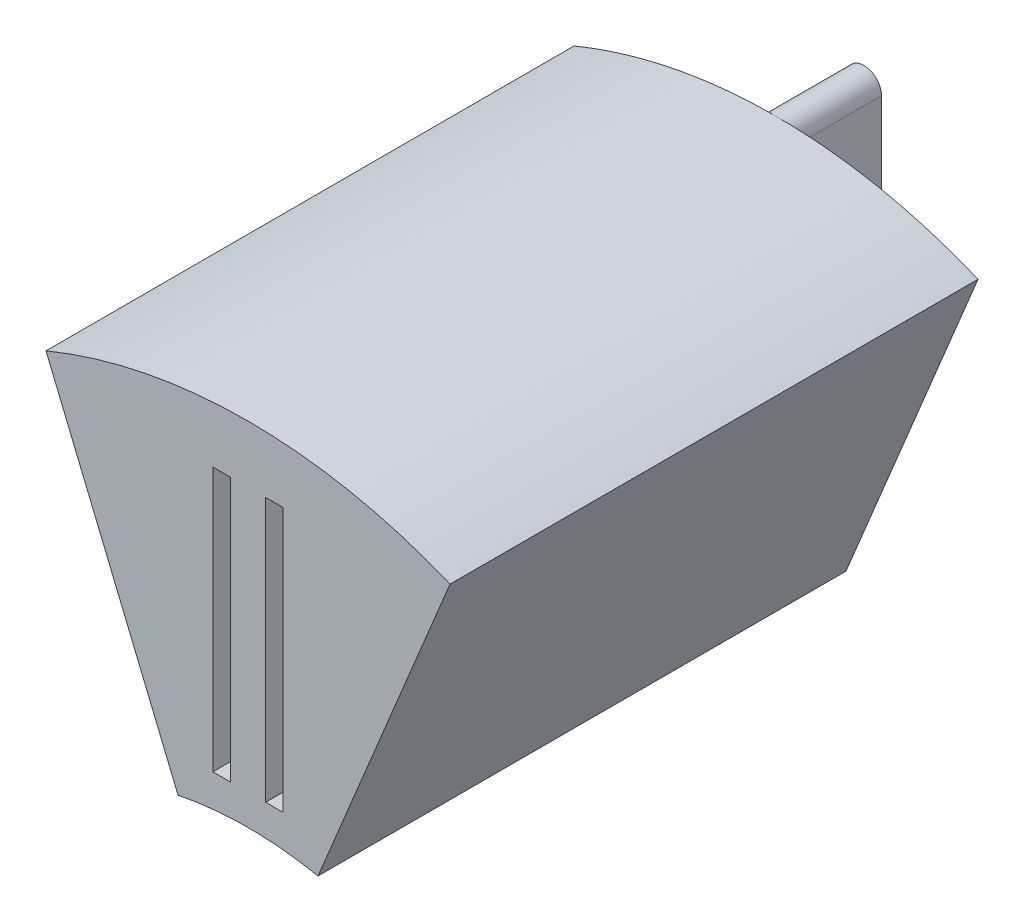
SolidWorks part; units mm, degrees
ref_plane "Ön Düzlem" through (0, 0, 0) normal (0, 0, 1) x (1, 0, 0)
ref_plane "Üst Düzlem" through (0, 0, 0) normal (0, 1, 0) x (1, 0, 0)
ref_plane "Sağ Düzlem" through (0, 0, 0) normal (1, 0, 0) x (0, 0, -1)
sketch "Sketch1" plane through (0, 0, 0) normal (0, 0, 1) x (1, 0, 0)
  line L0 (1.1481, 2.7716) -> (0.3827, 0.9239)
  line L6 (-1.1481, 2.7716) -> (-0.3827, 0.9239)
  line L7 (-1.1481, 2.7716) -> (0, 0) construction
  line L8 (0, 0) -> (1.1481, 2.7716) construction
  line L9 (-1.1481, 2.7716) -> (1.1481, 2.7716) construction
  arc A2 (0.3827, 0.9239) -> (-0.3827, 0.9239) centre (0, 0) ccw
  arc A3 (1.1481, 2.7716) -> (-1.1481, 2.7716) centre (0, 0) ccw
  point P1 (0, 2.7716)
  dimension "D1" = 1
  dimension "D2" = 3
  dimension "D4" = 45
extrude "Boss-Extrude1" add sketch "Sketch1" along normal blind 3
sketch "Sketch2" plane through (0, 0, 3) normal (0, 0, 1) x (1, 0, 0)
  line L0 (0, 2) -> (0, 2.9) construction
  line L1 (-0.1, 2) -> (-0.1, 2.9)
  line L2 (0.1, 2) -> (0.1, 2.9)
  arc A0 (-0.1, 2) -> (0.1, 2) centre (0, 2) ccw
  arc A1 (0.1, 2.9) -> (-0.1, 2.9) centre (0, 2.9) ccw
  arc A2 (1.1481, 2.7716) -> (-1.1481, 2.7716) centre (0, 0) ccw construction
  point P3 (0, 2.45)
  dimension "D1" = 0.1
  dimension "D2" = 0.9
extrude "Boss-Extrude2" add sketch "Sketch2" along normal blind 0.5
sketch "Sketch4" plane through (0.1, 0, 0) normal (1, 0, 0) x (0, 0, -1)
  line L0 (-3, 2.6739) -> (-3, 1.1739)
  line L1 (-3, 2) -> (-3, 2.9) construction
  line L2 (-3, 0.9239) -> (-3, 2.7716) construction
  line L3 (-3, 1.1739) -> (-1, 1.1739)
  line L4 (-1, 1.1739) -> (-3, 2.6739)
  line L5 (-3, 0.9239) -> (0, 0.9239) construction
  dimension "D1" = 1.5
  dimension "D2" = 2
  dimension "D3" = 0.25
extrude "Cut-Extrude1" cut sketch "Sketch4" against normal blind 0.3 and the other way blind 0.1
sketch "Sketch5" plane through (0, 0, 3) normal (0, 0, 1) x (1, 0, 0)
  line L0 (0.2, 1.1739) -> (-0.2, 1.1739) construction
  line L1 (-0.1, 2.6739) -> (0.1, 2.6739)
  line L2 (-0.1, 2.6739) -> (-0.1, 1.1739)
  line L3 (-0.1, 1.1739) -> (0.1, 1.1739)
  line L4 (0.1, 2.6739) -> (0.1, 1.1739)
  line L5 (0.1, 2) -> (0.1, 2.9) construction
extrude "Boss-Extrude3" add sketch "Sketch5" against normal blind 3
sketch "Sketch6" plane through (0, 0, 0) normal (0, 0, -1) x (-1, 0, 0)
  line L0 (0, 2) -> (0, 2.9) construction
  line L1 (-0.1, 2) -> (-0.1, 2.9)
  line L2 (0.1, 2) -> (0.1, 2.9)
  arc A0 (-0.1, 2) -> (0.1, 2) centre (0, 2) ccw
  arc A1 (0.1, 2.9) -> (-0.1, 2.9) centre (0, 2.9) ccw
  arc A2 (1.1481, 2.7716) -> (-1.1481, 2.7716) centre (0, 0) ccw construction
  point P3 (0, 2.45)
  dimension "D2" = 0.1
  dimension "D1" = 0.9
extrude "Boss-Extrude4" add sketch "Sketch6" along normal blind 0.5
sketch "Sketch7" plane through (0, 0, 3) normal (0, 0, 1) x (1, 0, 0)
  circle A0 centre (0, -1) radius 2
  dimension "D1" = 4
  dimension "D2" = 1
extrude "Cut-Extrude2" cut sketch "Sketch7" against normal blind 3
sketch "Sketch8" plane through (0, 0, 3.5) normal (0, 0, 1) x (1, 0, 0)
  line L1 (-1.3043, 2) -> (1.5208, 2)
  line L2 (-1.3043, 2) -> (-1.3043, 0.8608)
  line L3 (-1.3043, 0.8608) -> (1.5208, 0.8608)
  line L4 (1.5208, 2) -> (1.5208, 0.8608)
  arc A0 (0.1, 2.9) -> (-0.1, 2.9) centre (0, 2.9) ccw construction
  dimension "D1" = 0.9
extrude "Cut-Extrude3" cut sketch "Sketch8" against normal blind 0.5
sketch "Sketch9" plane through (0, 0, -0.5) normal (0, 0, -1) x (-1, 0, 0)
  line L1 (-1.5478, 2) -> (1.4315, 2)
  line L2 (-1.5478, 2) -> (-1.5478, 0.6497)
  line L3 (-1.5478, 0.6497) -> (1.4315, 0.6497)
  line L4 (1.4315, 2) -> (1.4315, 0.6497)
  arc A0 (0.1, 2.9) -> (-0.1, 2.9) centre (0, 2.9) ccw construction
  dimension "D1" = 0.9
extrude "Cut-Extrude4" cut sketch "Sketch9" against normal blind 0.5
sketch "Sketch10" plane through (0.1, 0, 0) normal (1, 0, 0) x (0, 0, -1)
  line L0 (-3, 0.9601) -> (-3, 2.7716) construction
  line L1 (-3.9799, 3.5381) -> (-3, 3.5381)
  line L2 (-3.9799, 3.5381) -> (-3.9799, 0.6967)
  line L3 (-3.9799, 0.6967) -> (-3, 0.6967)
  line L4 (-3, 3.5381) -> (-3, 0.6967)
extrude "Cut-Extrude5" cut sketch "Sketch10" against normal blind 2
